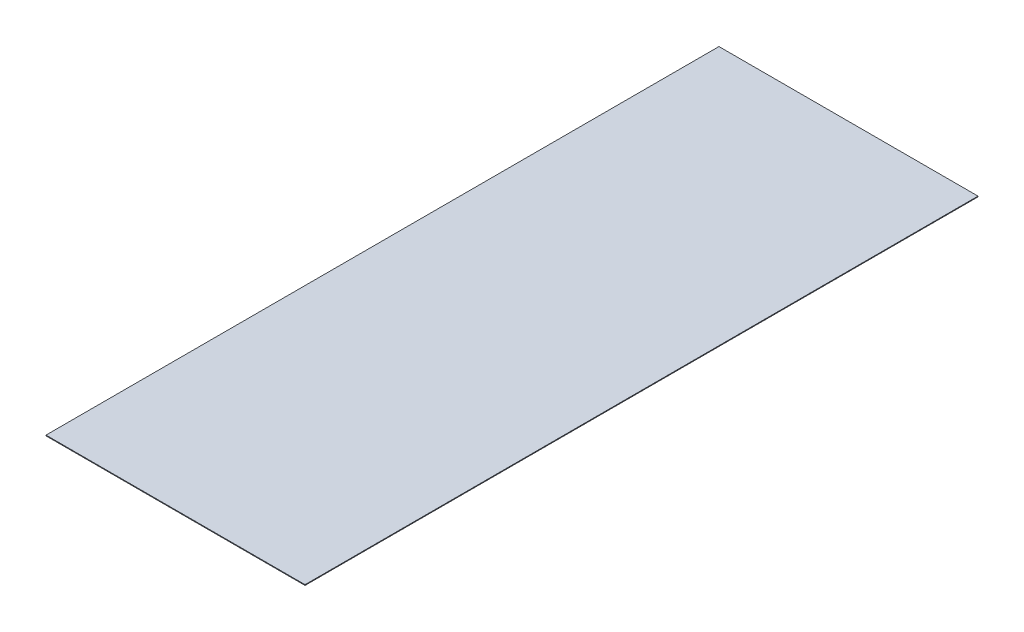
SolidWorks part; units mm, degrees
ref_plane "Front Plane" through (0, 0, 0) normal (0, 0, 1) x (1, 0, 0)
ref_plane "Top Plane" through (0, 0, 0) normal (0, 1, 0) x (1, 0, 0)
ref_plane "Right Plane" through (0, 0, 0) normal (1, 0, 0) x (0, 0, -1)
sketch "Sketch1" plane through (0, 0, 0) normal (0, 1, 0) x (1, 0, 0)
  line L1 (0, 0) -> (184, 0)
  line L2 (0, 0) -> (0, 478)
  line L3 (0, 478) -> (184, 478)
  line L4 (184, 0) -> (184, 478)
  dimension "D1" = 184
  dimension "D2" = 478
extrude "Boss-Extrude1" add sketch "Sketch1" along normal blind 0.5
